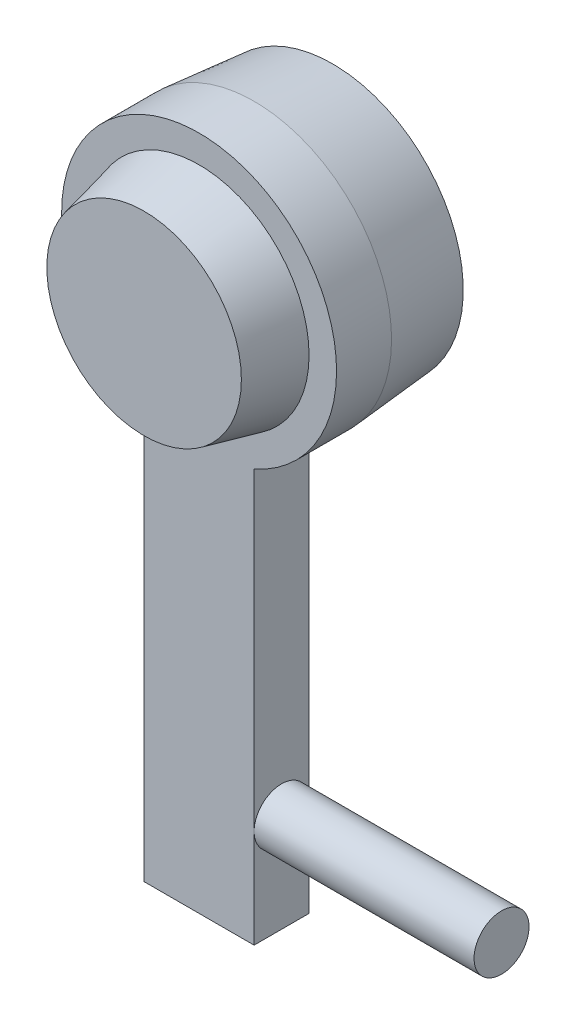
SolidWorks part; units mm, degrees
ref_plane "Ön Düzlem" through (0, 0, 0) normal (0, 0, 1) x (1, 0, 0)
ref_plane "Üst Düzlem" through (0, 0, 0) normal (0, 1, 0) x (1, 0, 0)
ref_plane "Sağ Düzlem" through (0, 0, 0) normal (1, 0, 0) x (0, 0, -1)
sketch "Sketch1" plane through (0, 0, 0) normal (0, 0, 1) x (1, 0, 0)
  line L0 (0, 0) -> (0, -97.9129) construction
  line L3 (-10, -22.9129) -> (-10, -97.9129)
  line L4 (-10, -97.9129) -> (10, -97.9129)
  line L5 (10, -22.9129) -> (10, -97.9129)
  arc A0 (10, -22.9129) -> (-10, -22.9129) centre (0, 0) ccw
  dimension "D1" = 50
  dimension "D2" = 20
  dimension "D3" = 75
extrude "Boss-Extrude1" add sketch "Sketch1" along normal mid plane 10
sketch "Sketch2" plane through (0, 0, 5) normal (0, 0, 1) x (1, 0, 0)
  circle A0 centre (0, 0) radius 20
  dimension "D1" = 40
extrude "Boss-Extrude2" add sketch "Sketch2" along normal blind 10 draft 13
sketch "Sketch3" plane through (0, 0, -5) normal (0, 0, -1) x (-1, 0, 0)
  circle A0 centre (0, 0) radius 22.5
  circle A1 centre (0, 0) radius 25
  arc A2 (10, -22.9129) -> (-10, -22.9129) centre (0, 0) ccw construction
  dimension "D1" = 45
extrude "Boss-Extrude3" add sketch "Sketch3" along normal blind 15 draft 5
sketch "Sketch4" plane through (10, 0, 0) normal (1, 0, 0) x (0, 0, -1)
  circle A0 centre (0, -80) radius 5
  dimension "D2" = 10
  dimension "D1" = 80
extrude "Boss-Extrude4" add sketch "Sketch4" along normal blind 40
